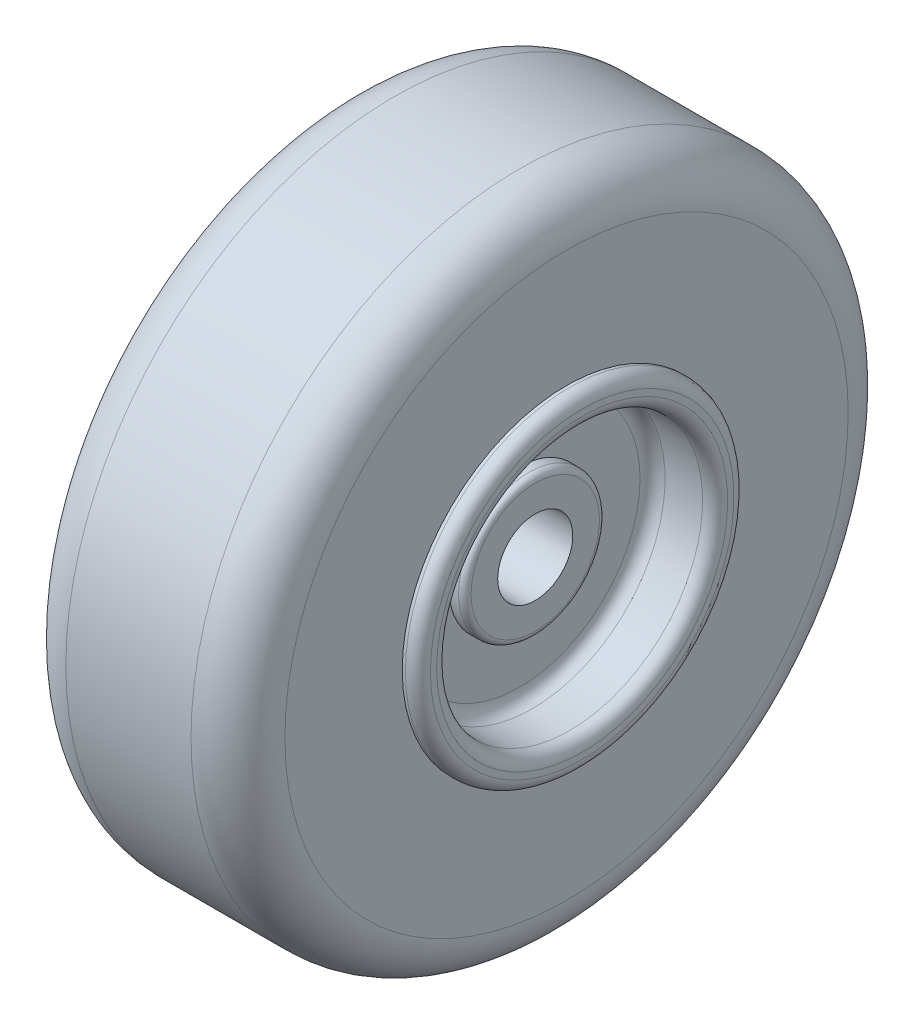
SolidWorks part; units mm, degrees
ref_plane "Plano frontal" through (0, 0, 0) normal (0, 0, 1) x (1, 0, 0)
ref_plane "Plano superior" through (0, 0, 0) normal (0, 1, 0) x (1, 0, 0)
ref_plane "Plano direito" through (0, 0, 0) normal (1, 0, 0) x (0, 0, -1)
sketch "Esboço1" plane through (0, 0, 0) normal (1, 0, 0) x (0, 0, -1)
  circle A0 centre (0, 0) radius 10.5
  circle A1 centre (0, 0) radius 1.75
  circle A2 centre (0, 0) radius 5.25
  dimension "D1" = 21
  dimension "D2" = 10.5
  dimension "D3" = 3.5
sketch "Esboço6" plane through (0, 0, 0) normal (0, 0, 1) x (1, 0, 0)
  line L0 (0, 0) -> (10.1982, 0) construction
  line L1 (2.5, 1.2) -> (2.5, 2.05)
  line L3 (0, 1.15) -> (0, 11.6959) construction
  line L4 (2.3, 2.25) -> (2, 2.25)
  line L9 (3.5, 5.25) -> (3.6, 5.25)
  line L10 (-2, 10.5) -> (2, 10.5)
  line L11 (3.5, 9) -> (3.5, 5.25)
  line L17 (3.6, 4.25) -> (2.4, 4.25)
  line L18 (2, 3.85) -> (2, 2.25)
  line L19 (4, 4.85) -> (4, 4.65)
  line L24 (-4, 4.85) -> (-4, 4.65)
  line L25 (-2, 3.85) -> (-2, 2.25)
  line L26 (-3.6, 4.25) -> (-2.4, 4.25)
  line L27 (-3.5, 9) -> (-3.5, 5.25)
  line L28 (-3.5, 5.25) -> (-3.6, 5.25)
  line L29 (-2.3, 2.25) -> (-2, 2.25)
  line L30 (-2.5, 1.2) -> (-2.5, 2.05)
  line L32 (-2.5, 1.2) -> (2.5, 1.2)
  arc A0 (2, 10.5) -> (3.5, 9) centre (2, 9) cw
  arc A1 (2.4, 4.25) -> (2, 3.85) centre (2.4, 3.85) ccw
  arc A2 (3.6, 4.25) -> (4, 4.65) centre (3.6, 4.65) ccw
  arc A3 (3.6, 5.25) -> (4, 4.85) centre (3.6, 4.85) cw
  arc A4 (2.5, 2.05) -> (2.3, 2.25) centre (2.3, 2.05) ccw
  arc A10 (-2.5, 2.05) -> (-2.3, 2.25) centre (-2.3, 2.05) cw
  arc A11 (-3.6, 5.25) -> (-4, 4.85) centre (-3.6, 4.85) ccw
  arc A12 (-3.6, 4.25) -> (-4, 4.65) centre (-3.6, 4.65) cw
  arc A13 (-2.4, 4.25) -> (-2, 3.85) centre (-2.4, 3.85) cw
  arc A14 (-2, 10.5) -> (-3.5, 9) centre (-2, 9) ccw
  point P5 (0, 1.75)
  point P6 (0, 5.25)
  point P7 (0, 10.5)
  point P20 (3.5, 10.5)
  point P51 (0, 10.5)
  dimension "D2" = 1.5
  dimension "D5" = 0
  dimension "D6" = 0.4
  dimension "D9" = 0.2
  dimension "D1" = 2
  dimension "D3" = 0.5
  dimension "D4" = 1
  dimension "D8" = 0.5
  dimension "D10" = 1.2
revolve "Revolução2" add sketch "Esboço6" angle 360 about L0
